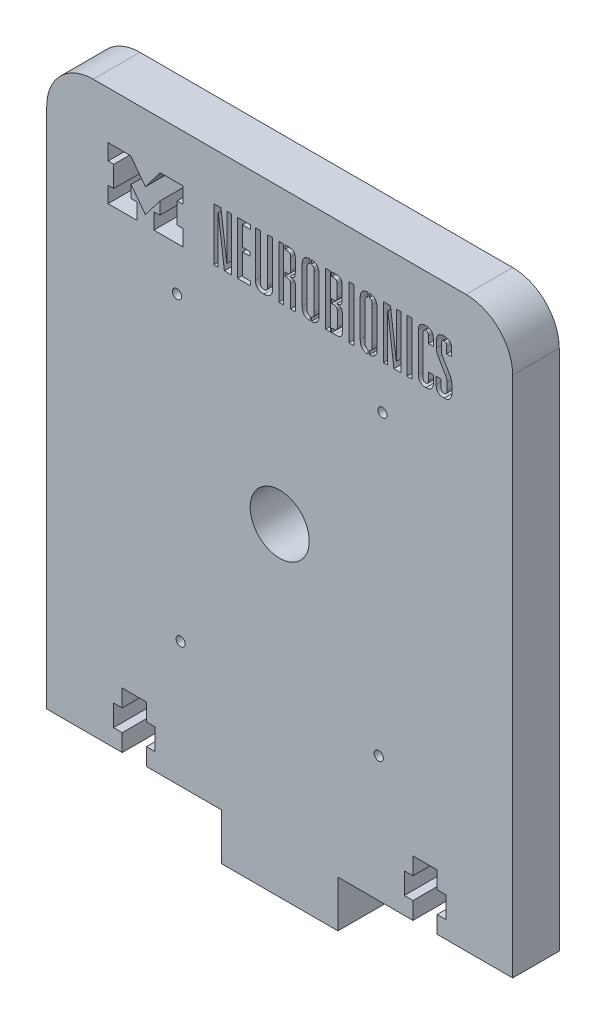
SolidWorks part; units mm, degrees
material "6061-T6 (SS)"
ref_plane "Front Plane" through (0, 0, 0) normal (0, 0, 1) x (1, 0, 0)
ref_plane "Top Plane" through (0, 0, 0) normal (0, 1, 0) x (1, 0, 0)
ref_plane "Right Plane" through (0, 0, 0) normal (1, 0, 0) x (0, 0, -1)
sketch "Sketch1" plane through (0, 0, 0) normal (0, 0, 1) x (1, 0, 0)
  line L1 (0, 0) -> (127, 0)
  line L2 (0, 0) -> (0, 155)
  line L3 (0, 155) -> (127, 155)
  line L4 (127, 0) -> (127, 155)
  dimension "D1" = 155
  dimension "D2" = 127
extrude "Boss-Extrude1" add sketch "Sketch1" along normal blind 12.7
sketch "Sketch2" plane through (0, 0, 12.7) normal (0, 0, 1) x (1, 0, 0)
  line L0 (63.5, 0) -> (63.5, 155) construction
  line L1 (0, 0) -> (127, 0) construction
  line L2 (127, 155) -> (0, 155) construction
  line L3 (23.876, 15.24) -> (23.876, 0) construction
  line L4 (20.574, 0) -> (27.178, 0)
  line L5 (20.574, 0) -> (20.574, 15.24)
  line L6 (20.574, 15.24) -> (27.178, 15.24)
  line L7 (27.178, 0) -> (27.178, 15.24)
  line L8 (18.2118, 10.541) -> (29.5402, 10.541)
  line L9 (18.2118, 10.541) -> (18.2118, 4.699)
  line L10 (18.2118, 4.699) -> (29.5402, 4.699)
  line L11 (29.5402, 10.541) -> (29.5402, 4.699)
  line L12 (18.2118, 7.62) -> (29.5402, 7.62) construction
  line L13 (108.7882, 7.62) -> (97.4598, 7.62) construction
  line L14 (103.124, 15.24) -> (103.124, 0) construction
  line L15 (97.4598, 10.541) -> (97.4598, 4.699)
  line L16 (108.7882, 4.699) -> (97.4598, 4.699)
  line L17 (108.7882, 10.541) -> (108.7882, 4.699)
  line L18 (108.7882, 10.541) -> (97.4598, 10.541)
  line L19 (99.822, 0) -> (99.822, 15.24)
  line L20 (106.426, 15.24) -> (99.822, 15.24)
  line L21 (106.426, 0) -> (106.426, 15.24)
  line L22 (106.426, 0) -> (99.822, 0)
  line L23 (0, 155) -> (0, 0) construction
  line M2 (0, 0) -> (127, 0)
  dimension "D1" = 6.604
  dimension "D2" = 11.3284
  dimension "D3" = 7.62
  dimension "D4" = 15.24
  dimension "D5" = 23.876
  dimension "D6" = 5.842
extrude "Cut-Extrude1" cut sketch "Sketch2" against normal through all contours L5 L8 L7 L6 | L5 L10 L7 L8 | L11 L8 L7 L10 | L9 L10 L5 L8 | L10 L5 L7 M2 | L21 L16 L19 M2 | L16 L21 L18 L19 | L21 L16 L17 L18 | L18 L21 L20 L19 | L16 L19 L18 L15
hole_wizard "1/4 Clearance Hole1" [suppressed] positions "Sketch5" profile "Sketch4" hole size "1/4" standard "ANSI Inch"
sketch "Sketch5" plane through (0, 0, 12.7) normal (0, 0, 1) x (1, 0, 0)
  line L4 (63.5, 150) -> (63.5, 0)
  line L5 (127, 150) -> (0, 150) construction
  line L6 (92.202, 0) -> (127, 0) construction
  point P9 (103.5, 25.4)
  point P13 (103.5, 76.2)
  dimension "D1" = 40
  dimension "D2" = 40
  dimension "D3" = 50.8
  dimension "D4" = 25.4
sketch "Sketch4" plane through (103.5, 25.4, 12.7) normal (1, 0, 0) x (0, -1, 0)
  line L0 (0, 0) -> (0, 27.4298)
  line L1 (0, 27.4298) -> (3.3782, 25.4)
  line L2 (3.3782, 25.4) -> (3.3782, 0)
  line L5 (3.3782, 0) -> (0, 0)
  line L10 (0, 27.4298) -> (-3.3782, 25.4) construction
  line L11 (0, -6.35) -> (0, 107.95) construction
  dimension "Hole Dia." = 6.7564
  dimension "Hole Depth" = 25.4
  dimension "Drill Angle" = 118
hole_wizard "CSK for 1/4 Flat Head Machine Screw2" [suppressed] positions "Sketch9" profile "Sketch8" countersink size "1/4" standard "Ansi Inch"
sketch "Sketch9" plane through (0, 0, 0) normal (0, 0, -1) x (-1, 0, 0)
  line L0 (-139.7, 174.498) -> (-127, 181.102) construction
  line L1 (-127, 155.702) -> (-139.7, 149.098) construction
  line L2 (-12.7, 149.098) -> (-25.4, 155.702) construction
  line L3 (-25.4, 181.102) -> (-12.7, 174.498) construction
  line L4 (-111.252, 114.3) -> (-104.648, 127) construction
  line L5 (-41.148, 127) -> (-47.752, 114.3) construction
  point P1 (-133.35, 177.8)
  point P5 (-133.35, 152.4)
  point P9 (-19.05, 152.4)
  point P13 (-19.05, 177.8)
  point P19 (-107.95, 120.65)
  point P23 (-44.45, 120.65)
sketch "Sketch8" plane through (133.35, 177.8, 0) normal (1, 0, 0) x (0, 1, 0)
  line L0 (0, 0) -> (0, 12.7)
  line L1 (0, 12.7) -> (3.2639, 12.7)
  line L2 (3.2639, 12.7) -> (3.2639, 3.6524)
  line L3 (3.2639, 3.6524) -> (6.4389, 0)
  line L5 (6.4389, 0) -> (0, 0)
  line L6 (-3.2639, 3.6524) -> (-6.4389, 0) construction
  line L11 (0, -6.35) -> (0, 107.95) construction
  dimension "Thru Hole Dia." = 6.5278
  dimension "Thru Hole Depth" = 12.7
  dimension "Near C'Sink Dia." = 12.8778
  dimension "Near C'Sink Angle" = 82
fillet "Fillet1" radius 12.7 2 edges at (127, 155, 6.35) (0, 155, 6.35)
sketch "Sketch11" plane through (0, 0, 0) normal (0, -1, 0) x (1, 0, 0)
  line L0 (27.178, 12.7) -> (99.822, 12.7) construction
  line L1 (47.625, 12.7) -> (79.375, 12.7)
  line L2 (47.625, 12.7) -> (47.625, 0)
  line L3 (47.625, 0) -> (79.375, 0)
  line L4 (79.375, 12.7) -> (79.375, 0)
  line L5 (27.178, 0) -> (99.822, 0) construction
  line L6 (63.5, 12.7) -> (63.5, 0) construction
  line L7 (27.178, 0) -> (27.178, 12.7) construction
  line L8 (99.822, 0) -> (99.822, 12.7) construction
  dimension "D1" = 31.75
extrude "Boss-Extrude2" add sketch "Sketch11" along normal blind 12.7
ref_plane "Plane1" through (63.5, 0, 0) normal (1, 0, 0) x (0, 0, -1)
mirror "Mirror2" [suppressed] about plane through (63.5, 0, 0) normal (1, 0, 0)
sketch "Sketch19" plane through (0, 0, 12.7) normal (0, 0, 1) x (1, 0, 0)
  line L4 (64.9193, 135.679) -> (64.9193, 134.5642)
  line L5 (64.5693, 140.9303) -> (64.5693, 142.0451)
  line L31 (46.7618, 140.4462) -> (46.7178, 140.4462)
  line L32 (58.2179, 142.0451) -> (58.2179, 130.0022)
  line L33 (74.2302, 139.7275) -> (74.2302, 129.9582)
  line L34 (77.3163, 134.5642) -> (77.3163, 128.7554)
  line L35 (94.6251, 127.6406) -> (92.9675, 140.4462)
  line L36 (104.0569, 129.5475) -> (104.0569, 131.5571)
  line L37 (107.5334, 140.0648) -> (107.5334, 138.554)
  line L38 (56.8977, 142.0451) -> (58.2179, 142.0451)
  line L39 (66.4421, 127.6406) -> (66.4421, 133.684)
  line L40 (76.0108, 127.6406) -> (76.0108, 142.0451)
  line L41 (85.4426, 129.9582) -> (85.4426, 139.7275)
  line L42 (99.5097, 142.0451) -> (99.5097, 127.6406)
  line L43 (47.4805, 142.0451) -> (49.0941, 129.7235)
  line L44 (53.3186, 135.679) -> (55.3869, 135.679)
  line L45 (66.3002, 135.1802) -> (66.3002, 135.1362)
  line L46 (80.4993, 140.3875) -> (80.4993, 136.7351)
  line L47 (77.3163, 140.9303) -> (77.3163, 135.679)
  line L48 (104.0569, 138.2753) -> (104.0569, 140.1235)
  line L49 (49.0941, 129.7235) -> (49.1381, 129.7235)
  line L50 (51.9984, 142.0451) -> (55.4895, 142.0451)
  line L51 (67.7964, 133.8014) -> (67.7964, 127.6406)
  line L52 (66.4933, 136.7204) -> (66.4933, 139.9475)
  line L53 (79.0618, 135.1802) -> (79.0618, 135.1362)
  line L54 (91.7647, 127.6406) -> (91.7647, 142.0451)
  line L55 (105.3771, 131.5571) -> (105.3771, 129.5035)
  line L56 (101.2699, 129.5035) -> (101.2699, 140.1529)
  line L57 (49.1381, 142.0451) -> (50.2969, 142.0451)
  line L58 (64.9193, 140.9303) -> (64.9193, 142.0451)
  line L59 (72.91, 129.9876) -> (72.91, 139.6835)
  line L60 (92.9235, 140.4462) -> (92.9235, 127.6406)
  line L61 (93.6863, 142.0451) -> (95.2998, 129.7235)
  line L62 (104.0569, 131.5571) -> (105.3771, 131.5571)
  line L63 (53.3186, 140.9303) -> (53.3186, 135.679)
  line L64 (55.4895, 128.7554) -> (55.4895, 127.6406)
  line L65 (64.9193, 135.679) -> (65.5105, 135.679)
  line L66 (78.0147, 140.9303) -> (77.6663, 140.9303)
  line L67 (88.7227, 129.9876) -> (88.7227, 139.6835)
  line L68 (105.3771, 140.1529) -> (105.3771, 138.2753)
  line L69 (107.8267, 137.2632) -> (109.9243, 133.6694)
  line L70 (60.2128, 130.0022) -> (60.2128, 142.0451)
  line L71 (63.2492, 142.0451) -> (64.5693, 142.0451)
  line L72 (78.1614, 134.5642) -> (77.6663, 134.5642)
  line L73 (86.7628, 139.6835) -> (86.7628, 129.9876)
  line L74 (110.3497, 138.3193) -> (109.0296, 138.3193)
  line L75 (50.2969, 127.6406) -> (48.4193, 127.6406)
  line L76 (55.4895, 140.9303) -> (53.3186, 140.9303)
  line L77 (65.3785, 140.9303) -> (64.9193, 140.9303)
  line L78 (79.1295, 136.7204) -> (79.1295, 139.9475)
  line L79 (83.6971, 142.0451) -> (83.6971, 127.6406)
  line L80 (98.1895, 127.6406) -> (98.1895, 142.0451)
  line L81 (109.0296, 140.0648) -> (109.0589, 140.0648)
  line L82 (55.4895, 142.0451) -> (55.4895, 140.9303)
  line L83 (55.4895, 127.6406) -> (51.9984, 127.6406)
  line L84 (60.2128, 142.0451) -> (61.5183, 142.0451)
  line L85 (78.4604, 127.6406) -> (77.6663, 127.6406)
  line L86 (82.3769, 142.0451) -> (83.6971, 142.0451)
  line L87 (109.0882, 129.7235) -> (109.0882, 131.7331)
  line L88 (108.7068, 133.112) -> (106.7706, 136.4857)
  line L89 (50.2969, 142.0451) -> (50.2969, 127.6406)
  line L90 (45.559, 142.0451) -> (47.4805, 142.0451)
  line L91 (64.5693, 127.6406) -> (63.2492, 127.6406)
  line L92 (70.9501, 139.6835) -> (70.9501, 129.9876)
  line L93 (92.9235, 127.6406) -> (91.7647, 127.6406)
  line L94 (95.2998, 129.7235) -> (95.3438, 129.7235)
  line L95 (106.1399, 129.6355) -> (106.1399, 131.6158)
  line L96 (48.4193, 127.6406) -> (46.7618, 140.4462)
  line L97 (45.559, 127.6406) -> (45.559, 142.0451)
  line L98 (64.9193, 142.0451) -> (65.6988, 142.0451)
  line L99 (69.63, 129.9582) -> (69.63, 139.7275)
  line L100 (96.5027, 142.0451) -> (96.5027, 127.6406)
  line L101 (91.7647, 142.0451) -> (93.6863, 142.0451)
  line L102 (99.5097, 127.6406) -> (98.1895, 127.6406)
  line L103 (106.1399, 131.6158) -> (107.46, 131.6158)
  line L104 (56.8977, 129.5769) -> (56.8977, 142.0451)
  line L105 (65.4153, 134.5642) -> (64.9193, 134.5642)
  line L106 (79.2028, 129.7382) -> (79.2028, 133.684)
  line L107 (90.0429, 139.7275) -> (90.0429, 129.9582)
  line L108 (102.5901, 140.1235) -> (102.5901, 129.5475)
  line L109 (55.3869, 134.5642) -> (53.3186, 134.5642)
  line L110 (64.5693, 140.9303) -> (64.5693, 127.6406)
  line L111 (80.558, 133.8014) -> (80.558, 129.2981)
  line L112 (77.6663, 135.679) -> (78.1467, 135.679)
  line L113 (105.3771, 138.2753) -> (104.0569, 138.2753)
  line L114 (109.0296, 138.3193) -> (109.0296, 140.0648)
  line L115 (55.3869, 135.679) -> (55.3869, 134.5642)
  line L116 (53.3186, 134.5642) -> (53.3186, 128.7554)
  line L117 (61.5183, 142.0451) -> (61.5183, 129.5769)
  line L118 (67.7964, 127.6406) -> (66.4421, 127.6406)
  line L119 (77.6663, 128.7554) -> (78.088, 128.7554)
  line L120 (83.6971, 127.6406) -> (82.3769, 127.6406)
  line L121 (110.3497, 140.1529) -> (110.3497, 138.3193)
  line L122 (46.7178, 140.4462) -> (46.7178, 127.6406)
  line L123 (49.1381, 129.7235) -> (49.1381, 142.0451)
  line L124 (67.7377, 140.3875) -> (67.7377, 136.7351)
  line L125 (76.0108, 142.0451) -> (77.3163, 142.0451)
  line L126 (82.3769, 127.6406) -> (82.3769, 142.0451)
  line L127 (95.3438, 129.7235) -> (95.3438, 142.0451)
  line L128 (106.2132, 138.3193) -> (106.2132, 140.0502)
  line L129 (46.7178, 127.6406) -> (45.559, 127.6406)
  line L130 (51.9984, 127.6406) -> (51.9984, 142.0451)
  line L131 (63.2492, 127.6406) -> (63.2492, 142.0451)
  line L132 (96.5027, 127.6406) -> (94.6251, 127.6406)
  line L133 (98.1895, 142.0451) -> (99.5097, 142.0451)
  line L134 (107.46, 131.6158) -> (107.46, 129.7235)
  line L135 (53.3186, 128.7554) -> (55.4895, 128.7554)
  line L136 (66.4421, 133.684) -> (66.4567, 133.684)
  line L137 (95.3438, 142.0451) -> (96.5027, 142.0451)
  line L138 (92.9675, 140.4462) -> (92.9235, 140.4462)
  line L139 (110.4084, 131.9092) -> (110.4084, 129.6355)
  line L142 (77.6663, 135.679) -> (77.6663, 134.5642)
  line L143 (77.3163, 140.9303) -> (77.3163, 142.0451)
  line L144 (77.3163, 135.679) -> (77.3163, 134.5642)
  line L145 (77.6663, 142.0451) -> (77.6663, 140.9303)
  line L146 (77.3163, 128.7554) -> (77.3163, 127.6406)
  line L147 (77.6663, 128.7554) -> (77.6663, 127.6406)
  line L148 (77.6663, 142.0451) -> (78.4604, 142.0451)
  line L149 (77.3163, 127.6406) -> (76.0108, 127.6406)
  line L150 (87.5677, 142.1583) -> (87.5677, 141.0219)
  line L151 (87.9177, 142.1583) -> (87.9177, 141.0219)
  line L152 (87.7427, 142.1624) -> (87.7427, 127.5233) construction
  line L153 (87.5677, 128.6492) -> (87.5677, 127.5274)
  line L154 (87.9177, 128.6492) -> (87.9177, 127.5274)
  line L155 (71.9301, 142.1624) -> (71.9301, 127.5233) construction
  line L156 (71.7551, 142.1583) -> (71.7551, 141.0219)
  line L157 (72.1051, 142.1583) -> (72.1051, 141.0219)
  line L158 (72.1051, 128.6492) -> (72.1051, 127.5274)
  line L159 (71.7551, 128.6492) -> (71.7551, 127.5274)
  spline S0 degree 3 poles (80.558, 129.2981) (80.558, 127.8606) (79.7806, 127.6406) (78.4604, 127.6406) knots 0 0 0 0 1 1 1 1
  spline S1 degree 3 poles (78.1467, 135.679) (78.7628, 135.679) (79.1295, 135.855) (79.1295, 136.7204) knots 0 0 0 0 1 1 1 1
  spline S2 degree 3 poles (108.2961, 127.5233) (106.844, 127.5233) (106.1399, 128.1834) (106.1399, 129.6355) knots 0 0 0 0 1 1 1 1
  spline S3 degree 3 poles (67.7377, 136.7351) (67.7377, 135.6203) (67.3123, 135.2389) (66.3002, 135.1802) knots 0 0 0 0 1 1 1 1
  spline S4 degree 3 poles (79.2028, 133.684) (79.2028, 134.3881) (78.7774, 134.5642) (78.1614, 134.5642) knots 0 0 0 0 1 1 1 1
  spline S5 degree 3 poles (109.0589, 140.0648) (109.0589, 140.6222) (108.9122, 141.0476) (108.2961, 141.0476) knots 0 0 0 0 1 1 1 1
  spline S6 degree 3 poles (108.2815, 142.1624) (109.763, 142.1624) (110.3497, 141.4583) (110.3497, 140.1529) knots 0 0 0 0 1 1 1 1
  spline S7 degree 3 poles (58.2179, 130.0022) (58.2179, 128.9608) (58.5552, 128.6527) (59.2153, 128.6527) knots 0 0 0 0 1 1 1 1
  spline S8 degree 3 poles (66.3002, 135.1362) (67.239, 135.0775) (67.7964, 134.7988) (67.7964, 133.8014) knots 0 0 0 0 1 1 1 1
  spline S9 degree 3 poles (65.5105, 135.679) (66.1266, 135.679) (66.4933, 135.855) (66.4933, 136.7204) knots 0 0 0 0 1 1 1 1
  spline S10 degree 3 poles (102.5901, 129.5475) (102.5901, 128.9314) (102.8101, 128.6234) (103.3235, 128.6234) knots 0 0 0 0 1 1 1 1
  spline S11 degree 3 poles (103.3235, 142.1478) (104.7023, 142.1478) (105.3771, 141.3703) (105.3771, 140.1529) knots 0 0 0 0 1 1 1 1
  spline S12 degree 3 poles (66.4933, 139.9475) (66.4933, 140.7836) (66.0532, 140.9303) (65.3785, 140.9303) knots 0 0 0 0 1 1 1 1
  spline S13 degree 3 poles (87.9177, 128.6492) (88.5867, 128.7311) (88.7227, 129.2605) (88.7227, 129.9876) knots 0.082067 0.082067 0.082067 0.082067 1 1 1 1
  spline S14 degree 3 poles (74.2302, 129.9582) (74.2302, 128.5882) (73.727, 127.5989) (72.1051, 127.5274) knots 0 0 0 0 0.962899 0.962899 0.962899 0.962899
  spline S15 degree 3 poles (87.5677, 141.0219) (86.8987, 140.9399) (86.7628, 140.4106) (86.7628, 139.6835) knots 0.082067 0.082067 0.082067 0.082067 1 1 1 1
  spline S16 degree 3 poles (103.3235, 141.0476) (102.8101, 141.0476) (102.5901, 140.7543) (102.5901, 140.1235) knots 0 0 0 0 1 1 1 1
  spline S17 degree 3 poles (107.5334, 138.554) (107.5334, 138.0993) (107.6067, 137.6299) (107.8267, 137.2632) knots 0 0 0 0 1 1 1 1
  spline S18 degree 3 poles (87.9177, 142.1583) (89.5396, 142.0868) (90.0429, 141.0975) (90.0429, 139.7275) knots 0.037101 0.037101 0.037101 0.037101 1 1 1 1
  spline S19 degree 3 poles (87.5677, 127.5274) (85.9458, 127.5989) (85.4426, 128.5882) (85.4426, 129.9582) knots 0.037102 0.037102 0.037102 0.037102 1 1 1 1
  spline S20 degree 3 poles (101.2699, 140.1529) (101.2699, 141.3703) (101.9447, 142.1478) (103.3235, 142.1478) knots 0 0 0 0 1 1 1 1
  spline S21 degree 3 poles (59.186, 127.5233) (58.0859, 127.5233) (56.8977, 127.978) (56.8977, 129.5769) knots 0 0 0 0 1 1 1 1
  spline S22 degree 3 poles (71.7551, 127.5274) (70.1332, 127.5989) (69.63, 128.5882) (69.63, 129.9582) knots 0.037101 0.037101 0.037101 0.037101 1 1 1 1
  spline S23 degree 3 poles (71.7551, 141.0219) (71.0861, 140.9399) (70.9501, 140.4106) (70.9501, 139.6835) knots 0.082067 0.082067 0.082067 0.082067 1 1 1 1
  spline S24 degree 3 poles (108.2961, 141.0476) (107.6801, 141.0476) (107.5334, 140.6222) (107.5334, 140.0648) knots 0 0 0 0 1 1 1 1
  spline S25 degree 3 poles (110.4084, 129.6355) (110.4084, 128.286) (109.6163, 127.5233) (108.2961, 127.5233) knots 0 0 0 0 1 1 1 1
  spline S26 degree 3 poles (72.1051, 142.1583) (73.727, 142.0868) (74.2302, 141.0975) (74.2302, 139.7275) knots 0.037101 0.037101 0.037101 0.037101 1 1 1 1
  spline S27 degree 3 poles (70.9501, 129.9876) (70.9501, 129.2605) (71.0861, 128.7311) (71.7551, 128.6492) knots 0 0 0 0 0.917933 0.917933 0.917933 0.917933
  spline S28 degree 3 poles (78.088, 128.7554) (78.7628, 128.7554) (79.2028, 128.9021) (79.2028, 129.7382) knots 0 0 0 0 1 1 1 1
  spline S29 degree 3 poles (109.9243, 133.6694) (110.2177, 133.1706) (110.4084, 132.5546) (110.4084, 131.9092) knots 0 0 0 0 1 1 1 1
  spline S30 degree 3 poles (80.4993, 136.7351) (80.4993, 135.6203) (80.0739, 135.2242) (79.0618, 135.1802) knots 0 0 0 0 1 1 1 1
  spline S31 degree 3 poles (86.7628, 129.9876) (86.7628, 129.2605) (86.8987, 128.7311) (87.5677, 128.6492) knots 0 0 0 0 0.917933 0.917933 0.917933 0.917933
  spline S32 degree 3 poles (106.2132, 140.0502) (106.2132, 141.473) (106.9466, 142.1624) (108.2815, 142.1624) knots 0 0 0 0 1 1 1 1
  spline S33 degree 3 poles (59.2153, 128.6527) (59.8901, 128.6527) (60.2128, 128.9755) (60.2128, 130.0022) knots 0 0 0 0 1 1 1 1
  spline S34 degree 3 poles (90.0429, 129.9582) (90.0429, 128.5882) (89.5396, 127.5989) (87.9177, 127.5274) knots 0 0 0 0 0.962899 0.962899 0.962899 0.962899
  spline S35 degree 3 poles (108.2961, 128.6527) (108.8389, 128.6527) (109.0882, 129.0488) (109.0882, 129.7235) knots 0 0 0 0 1 1 1 1
  spline S36 degree 3 poles (106.7706, 136.4857) (106.4186, 137.1018) (106.2132, 137.5859) (106.2132, 138.3193) knots 0 0 0 0 1 1 1 1
  spline S37 degree 3 poles (72.1051, 128.6492) (72.7741, 128.7311) (72.91, 129.2605) (72.91, 129.9876) knots 0.082067 0.082067 0.082067 0.082067 1 1 1 1
  spline S38 degree 3 poles (85.4426, 139.7275) (85.4426, 141.0975) (85.9458, 142.0868) (87.5677, 142.1583) knots 0 0 0 0 0.962898 0.962898 0.962898 0.962898
  spline S39 degree 3 poles (61.5183, 129.5769) (61.5183, 127.978) (60.3155, 127.5233) (59.186, 127.5233) knots 0 0 0 0 1 1 1 1
  spline S40 degree 3 poles (79.1295, 139.9475) (79.1295, 140.7836) (78.6894, 140.9303) (78.0147, 140.9303) knots 0 0 0 0 1 1 1 1
  spline S41 degree 3 poles (103.3235, 128.6234) (103.8369, 128.6234) (104.0569, 128.9168) (104.0569, 129.5475) knots 0 0 0 0 1 1 1 1
  spline S42 degree 3 poles (105.3771, 129.5035) (105.3771, 128.286) (104.7023, 127.5086) (103.3235, 127.5086) knots 0 0 0 0 1 1 1 1
  spline S43 degree 3 poles (72.91, 139.6835) (72.91, 140.4106) (72.7741, 140.9399) (72.1051, 141.0219) knots 0 0 0 0 0.917933 0.917933 0.917933 0.917933
  spline S44 degree 3 poles (88.7227, 139.6835) (88.7227, 140.4106) (88.5867, 140.9399) (87.9177, 141.0219) knots 0 0 0 0 0.917933 0.917933 0.917933 0.917933
  spline S45 degree 3 poles (107.46, 129.7235) (107.46, 129.0488) (107.7241, 128.6527) (108.2961, 128.6527) knots 0 0 0 0 1 1 1 1
  spline S46 degree 3 poles (109.0882, 131.7331) (109.0882, 132.2319) (108.9855, 132.6132) (108.7068, 133.112) knots 0 0 0 0 1 1 1 1
  spline S47 degree 3 poles (65.6988, 142.0451) (66.9603, 142.0451) (67.7377, 141.8251) (67.7377, 140.3875) knots 0 0 0 0 1 1 1 1
  spline S48 degree 3 poles (69.63, 139.7275) (69.63, 141.0975) (70.1332, 142.0868) (71.7551, 142.1583) knots 0 0 0 0 0.962899 0.962899 0.962899 0.962899
  spline S49 degree 3 poles (78.4604, 142.0451) (79.7219, 142.0451) (80.4993, 141.8251) (80.4993, 140.3875) knots 0 0 0 0 1 1 1 1
  spline S50 degree 3 poles (66.4567, 133.684) (66.4567, 134.3881) (66.0313, 134.5642) (65.4153, 134.5642) knots 0 0 0 0 1 1 1 1
  spline S51 degree 3 poles (79.0618, 135.1362) (79.9859, 135.0922) (80.558, 134.7988) (80.558, 133.8014) knots 0 0 0 0 1 1 1 1
  spline S52 degree 3 poles (104.0569, 140.1235) (104.0569, 140.7396) (103.8369, 141.0476) (103.3235, 141.0476) knots 0 0 0 0 1 1 1 1
  spline S53 degree 3 poles (103.3235, 127.5086) (101.9447, 127.5086) (101.2699, 128.286) (101.2699, 129.5035) knots 0 0 0 0 1 1 1 1
  dimension "D1" = 0.35
  dimension "D2" = 0.35
  dimension "D3" = 0.175
  dimension "D4" = 0.175
  dimension "D5" = 0.175
  dimension "D6" = 0.175
sketch "Sketch20" plane through (0, 0, 12.7) normal (0, 0, 1) x (1, 0, 0)
  line L0 (7.2814, 142.1428) -> (71.0354, 142.1428) construction
  line L1 (7.2814, 127.6014) -> (73.4515, 127.6014) construction
  line L7 (22.9767, 131.9734) -> (24.6043, 131.9734)
  line L8 (24.6043, 131.9734) -> (24.6043, 127.6406)
  line L9 (24.6043, 127.6406) -> (16.7149, 127.6406)
  line L10 (16.7149, 127.6406) -> (16.7149, 131.9734)
  line L11 (16.7149, 131.9734) -> (18.2543, 131.9734)
  line L12 (18.2543, 131.9734) -> (18.2543, 137.7006)
  line L13 (18.2543, 137.7006) -> (16.7141, 137.7006)
  line L14 (16.7141, 137.7006) -> (16.7141, 142.0451)
  line L15 (16.7141, 142.0451) -> (22.8903, 142.0451)
  line L16 (22.8903, 142.0451) -> (26.9017, 136.7302)
  line L17 (26.9017, 136.7302) -> (30.913, 142.0451)
  line L18 (30.913, 142.0451) -> (37.0893, 142.0451)
  line L19 (37.0893, 142.0451) -> (37.0893, 137.7006)
  line L20 (37.0893, 137.7006) -> (35.549, 137.7006)
  line L21 (35.549, 137.7006) -> (35.549, 131.9734)
  line L22 (35.549, 131.9734) -> (37.0885, 131.9734)
  line L23 (37.0885, 131.9734) -> (37.0885, 127.6406)
  line L24 (37.0885, 127.6406) -> (29.1991, 127.6406)
  line L25 (29.1991, 127.6406) -> (29.1991, 131.9734)
  line L26 (29.1991, 131.9734) -> (30.8267, 131.9734)
  line L27 (30.8267, 131.9734) -> (30.8267, 135.3211)
  line L28 (30.8267, 135.3211) -> (26.9017, 130.1206)
  line L29 (26.9017, 130.1206) -> (22.9767, 135.3211)
  line L30 (22.9767, 135.3211) -> (22.9767, 131.9734)
extrude "Cut-Extrude9" cut sketch "Sketch20" against normal through all
extrude "Cut-Extrude10" cut sketch "Sketch19" against normal through all
sketch "Sketch21" plane through (0, 0, 12.7) normal (0, 0, 1) x (1, 0, 0)
  line L0 (0, 75.3826) -> (127, 75.3826) construction
  line L1 (0, 142.3) -> (0, 0) construction
  line L2 (127, 0) -> (127, 142.3) construction
  line L3 (79.375, -12.7) -> (47.625, -12.7) construction
  circle A0 centre (63.5, 75.3826) radius 8.05
  dimension "D2" = 16.1
  dimension "D1" = 88.0826
extrude "Cut-Extrude11" cut sketch "Sketch21" against normal through all contours A0
hole_wizard "M3x0.5 Tapped Hole1" positions "Sketch23" profile "Sketch24" tap size "M3x0.5" standard "ANSI Metric" end condition through all
sketch "Sketch23" plane through (0, 0, 12.7) normal (0, 0, 1) x (1, 0, 0)
  line L1 (63.5, -12.7) -> (63.5, 155) construction
  line L2 (79.375, -12.7) -> (47.625, -12.7) construction
  line L3 (114.3, 155) -> (12.7, 155) construction
  circle A0 centre (63.5, 75.3826) radius 6.2351 construction
  point P2 (35.5, 115.7207)
  point P4 (36.5, 34.21)
  dimension "D1" = 41.1726
  dimension "D2" = 27
  dimension "D3" = 28
  dimension "D4" = 40.3381
sketch "Sketch24" plane through (35.5, 115.7207, 12.7) normal (1, 0, 0) x (0, -1, 0)
  line L0 (0, 0) -> (0, 12.7)
  line L1 (0, 12.7) -> (1.25, 12.7)
  line L2 (1.25, 12.7) -> (1.25, 0)
  line L5 (1.25, 0) -> (0, 0)
  line L11 (0, -6.35) -> (0, 107.95) construction
  dimension "Thru Tap Drill Dia." = 2.5
  dimension "Thru Tap Drill Depth" = 12.7
cosmetic thread "Hole Thread2" parameters "D2"=3
cosmetic thread "Hole Thread3" parameters "D2"=3
mirror "Mirror3" about plane through (63.5, 0, 0) normal (1, 0, 0) of "M3x0.5 Tapped Hole1"
fillet "Fillet2" radius 0.25 2 edges at (24.6043, 131.9734, 6.35) (29.1991, 131.9734, 6.35)
sketch "Sketch25" plane through (0, -12.7, 0) normal (0, -1, 0) x (1, 0, 0)
  point P4 (63.5, 6.35)
